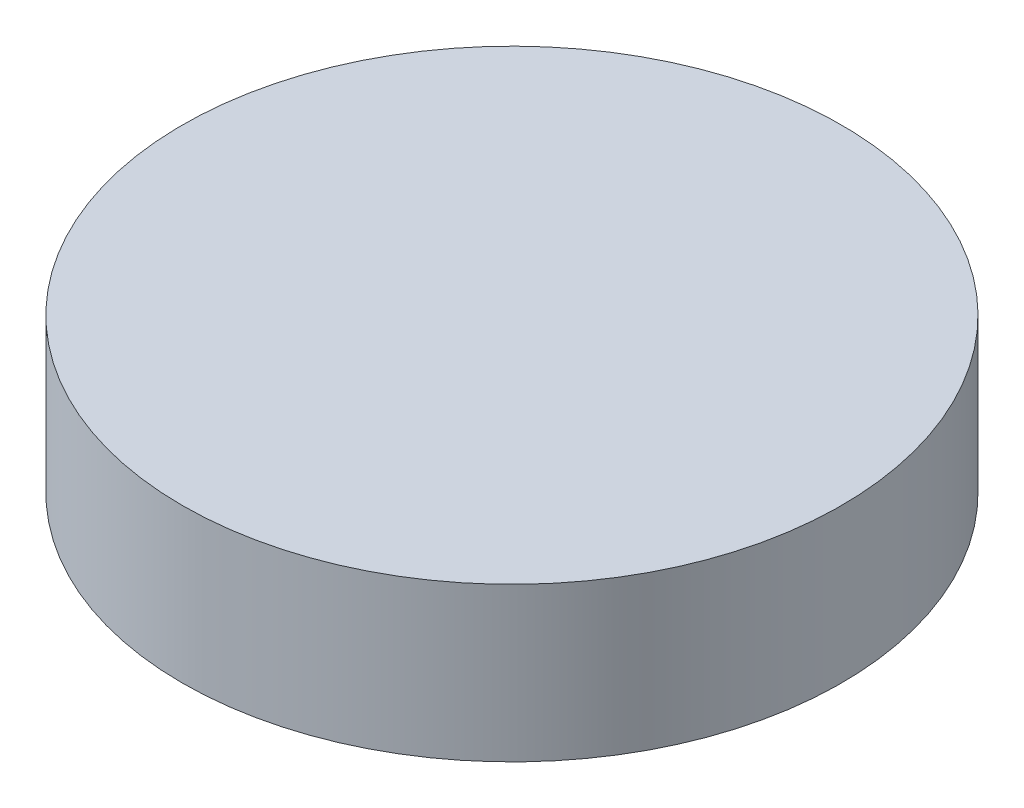
SolidWorks part; units mm, degrees
ref_plane "Front Plane" through (0, 0, 0) normal (0, 0, 1) x (1, 0, 0)
ref_plane "Top Plane" through (0, 0, 0) normal (0, 1, 0) x (1, 0, 0)
ref_plane "Right Plane" through (0, 0, 0) normal (1, 0, 0) x (0, 0, -1)
sketch "Sketch1" plane through (0, 0, 0) normal (0, 1, 0) x (1, 0, 0)
  circle A0 centre (0, 0) radius 10.5
extrude "Boss-Extrude1" add sketch "Sketch1" along normal blind 4.9 contours A0
